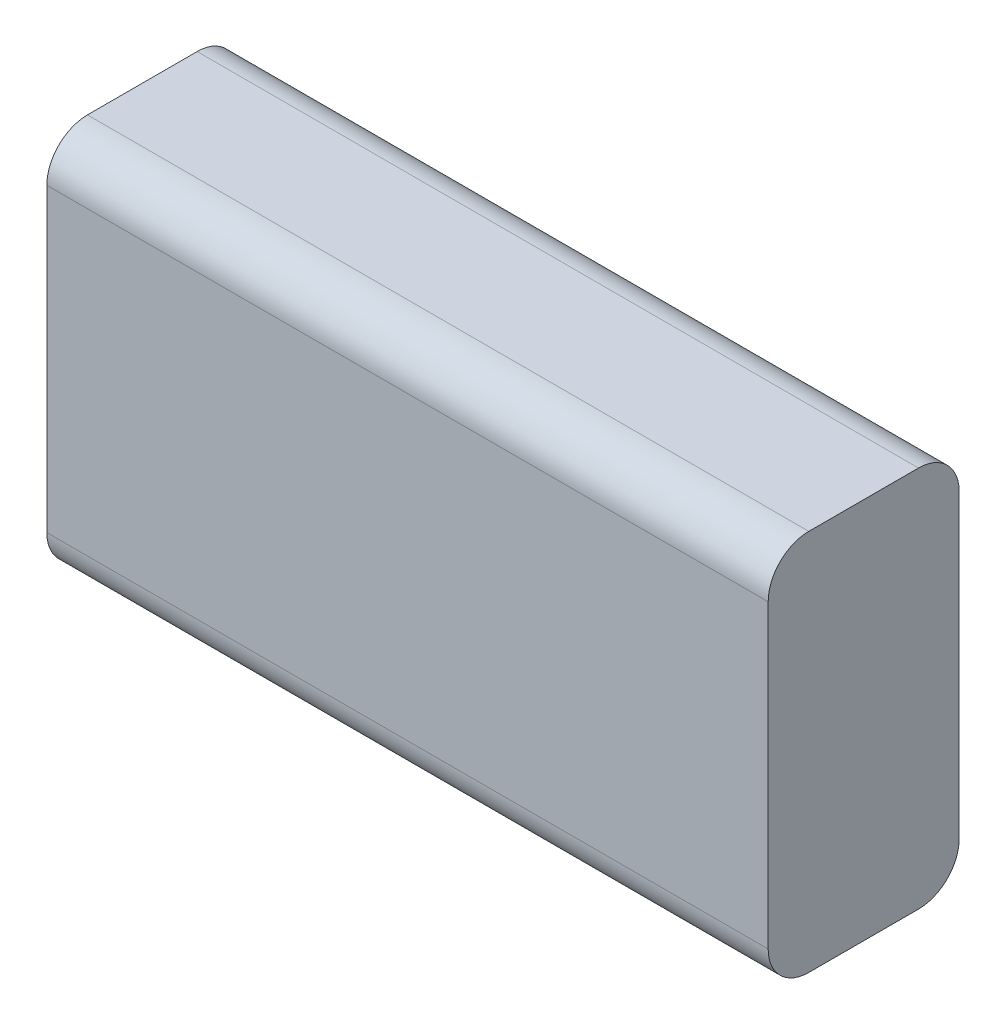
SolidWorks part; units mm, degrees
ref_plane "Plan de face" through (0, 0, 0) normal (0, 0, 1) x (1, 0, 0)
ref_plane "Plan de dessus" through (0, 0, 0) normal (0, 1, 0) x (1, 0, 0)
ref_plane "Plan de droite" through (0, 0, 0) normal (1, 0, 0) x (0, 0, -1)
sketch "Esquisse1" plane through (0, 0, 0) normal (0, 0, 1) x (1, 0, 0)
  line L1 (27.947, -20.2775) -> (-43.053, -20.2775)
  line L2 (27.947, -20.2775) -> (27.947, 17.3225)
  line L3 (27.947, 17.3225) -> (-43.053, 17.3225)
  line L4 (-43.053, -20.2775) -> (-43.053, 17.3225)
  dimension "D1" = 71
  dimension "D2" = 37.6
extrude "Extrusion1" add sketch "Esquisse1" along normal blind 18.8
fillet "Congé1" radius 4 1 edges at (-7.553, 17.3225, 18.8)
fillet "Congé2" radius 4 2 edges at (-7.553, -20.2775, 18.8) (-7.553, 17.3225, 0)
fillet "Congé3" radius 4 1 edges at (-7.553, -20.2775, 0)
